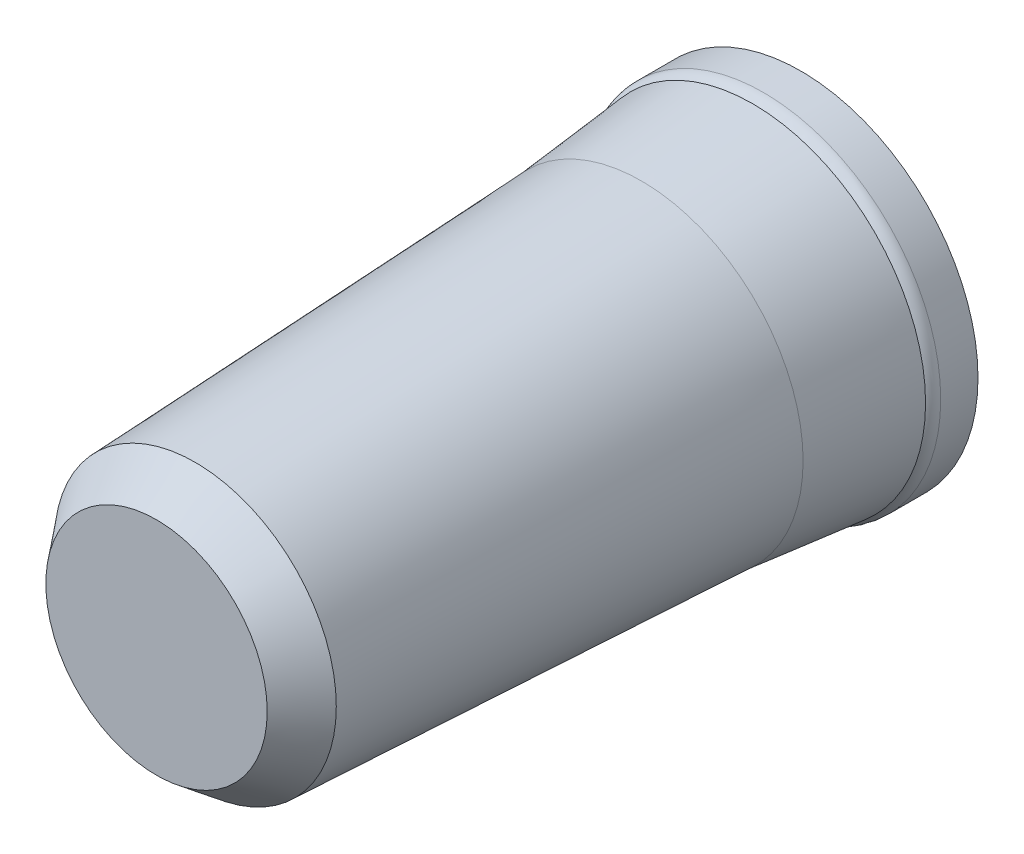
SolidWorks part; units mm, degrees
ref_plane "Front Plane" through (0, 0, 0) normal (0, 0, 1) x (1, 0, 0)
ref_plane "Top Plane" through (0, 0, 0) normal (0, 1, 0) x (1, 0, 0)
ref_plane "Right Plane" through (0, 0, 0) normal (1, 0, 0) x (0, 0, -1)
sketch "Sketch1" plane through (0, 0, 0) normal (1, 0, 0) x (0, 0, -1)
  line L0 (0, 0) -> (0, 22.1)
  line L1 (0, 22.1) -> (-4.6512, 22.1)
  line L2 (-5.9988, 21.5576) -> (-19.8759, 20.1546)
  line L3 (-19.8759, 20.1546) -> (-75.5572, 17.5968)
  line L4 (-75.5572, 17.5968) -> (-80.39, 13.8101)
  line L5 (-80.39, 13.8101) -> (-80.39, 0)
  line L6 (-80.39, 0) -> (0, 0)
  line L7 (0, 0) -> (50000, 0) construction
  arc A0 (-4.6512, 22.1) -> (-5.9988, 21.5576) centre (-4.6512, 20.1546) ccw
  dimension "D1" = 80.39
  dimension "D2" = 44.2
revolve "Revolve1" add sketch "Sketch1" angle 360 about L7
